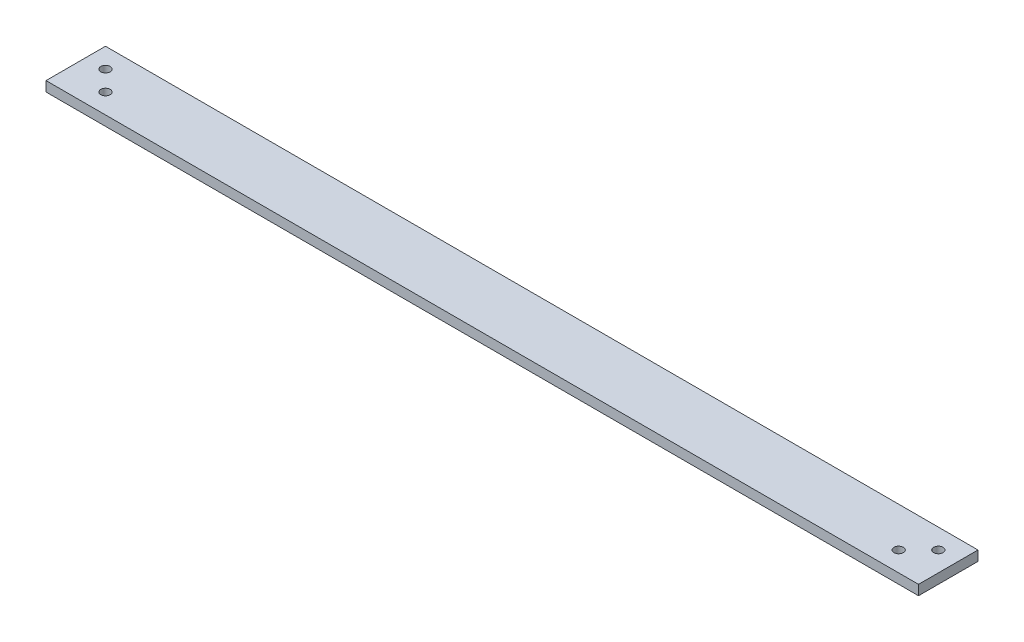
SolidWorks part; units mm, degrees
material "5052-H32"
ref_plane "Front Plane" through (0, 0, 0) normal (0, 0, 1) x (1, 0, 0)
ref_plane "Top Plane" through (0, 0, 0) normal (0, 1, 0) x (1, 0, 0)
ref_plane "Right Plane" through (0, 0, 0) normal (1, 0, 0) x (0, 0, -1)
sketch "Sketch1" plane through (0, 0, 0) normal (0, 1, 0) x (1, 0, 0)
  line L1 (139.7, -9.525) -> (-139.7, -9.525)
  line L2 (139.7, -9.525) -> (139.7, 9.525)
  line L3 (139.7, 9.525) -> (-139.7, 9.525)
  line L4 (-139.7, -9.525) -> (-139.7, 9.525)
  line L5 (139.7, -9.525) -> (-139.7, 9.525) construction
  line L6 (139.7, 9.525) -> (-139.7, -9.525) construction
  point P0 (0, 0)
  dimension "D1" = 279.4
  dimension "D2" = 19.05
extrude "Boss-Extrude1" add sketch "Sketch1" along normal blind 3.175 contours L3 L4 L1 L2
sketch "Sketch4" plane through (0, 3.175, 0) normal (0, 1, 0) x (1, 0, 0)
  line L0 (-120.65, 9.525) -> (-120.65, -9.525) construction
  line L1 (139.7, 9.525) -> (-139.7, 9.525) construction
  line L2 (139.7, -9.525) -> (-139.7, -9.525) construction
  line L3 (-120.65, -9.525) -> (-139.7, -9.525) construction
  line L4 (-139.7, 9.525) -> (-133.35, 3.175) construction
  line L5 (-133.35, 3.175) -> (-127, -3.175) construction
  line L6 (-127, -3.175) -> (-120.65, -9.525) construction
  circle A0 centre (-133.35, 3.175) radius 1.5
  circle A1 centre (-127, -3.175) radius 1.5
  dimension "D1" = 3
extrude "Cut-Extrude2" cut sketch "Sketch4" against normal through all
mirror "Mirror1" about plane through (0, 0, 0) normal (1, 0, 0) of "Cut-Extrude2"
